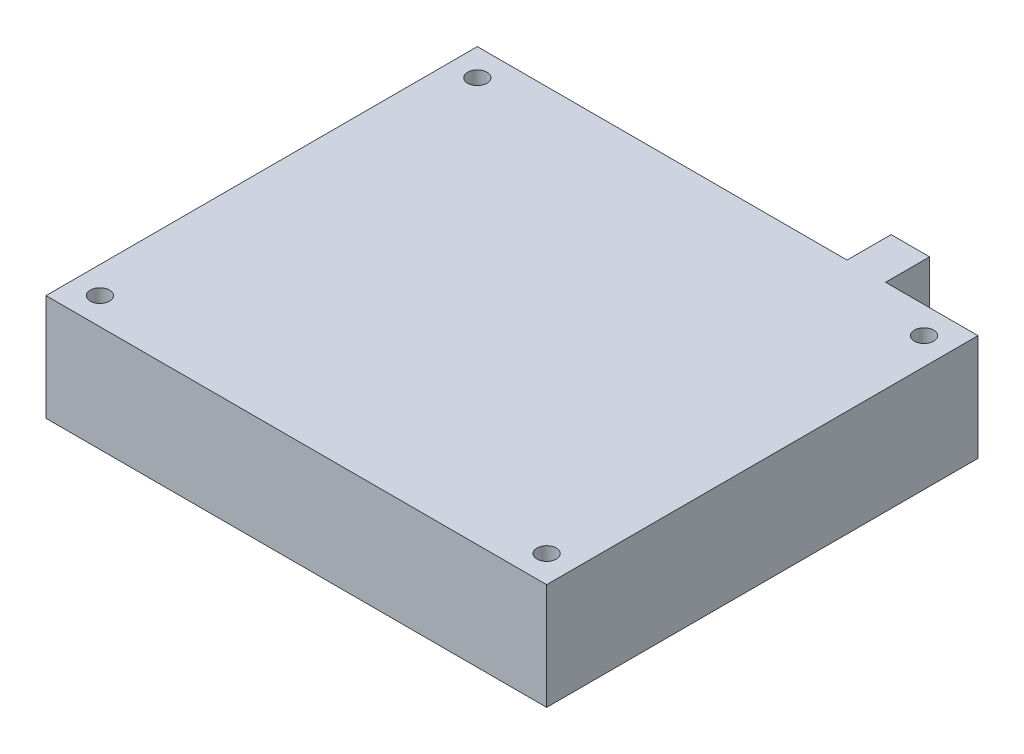
SolidWorks part; units mm, degrees
material "聚脂树脂"
ref_plane "前视基准面" through (0, 0, 0) normal (0, 0, 1) x (1, 0, 0)
ref_plane "上视基准面" through (0, 0, 0) normal (0, 1, 0) x (1, 0, 0)
ref_plane "右视基准面" through (0, 0, 0) normal (1, 0, 0) x (0, 0, -1)
other "Configuration Table"
sketch "草图1" plane through (0, 0, 0) normal (0, 1, 0) x (1, 0, 0)
  line L0 (0, 0) -> (0, 37.0245) construction
  line L1 (-32.5, -28) -> (32.5, -28)
  line L2 (-32.5, -28) -> (-32.5, 28)
  line L3 (-32.5, 28) -> (32.5, 28)
  line L4 (32.5, -28) -> (32.5, 28)
  line L5 (-32.5, -28) -> (32.5, 28) construction
  line L6 (-32.5, 28) -> (32.5, -28) construction
  line L7 (0, 0) -> (44.4454, 0) construction
  circle A0 centre (-29, 24.5) radius 1.25
  circle A1 centre (29, 24.5) radius 1.25
  circle A2 centre (29, -24.5) radius 1.25
  circle A3 centre (-29, -24.5) radius 1.25
  point P0 (0, 0)
  dimension "D3" = 2.5
  dimension "D4" = 58
  dimension "D5" = 49
  dimension "D1" = 65
  dimension "D2" = 56
extrude "凸台-拉伸1" add sketch "草图1" along normal blind 13.8
sketch "草图2" plane through (0, 13.8, 0) normal (0, 1, 0) x (1, 0, 0)
  line L0 (15.5, 28) -> (15.5, 33.72)
  line L1 (32.5, 28) -> (-32.5, 28) construction
  line L2 (15.5, 33.72) -> (20.5, 33.72)
  line L3 (20.5, 33.72) -> (20.5, 28)
  line L4 (20.5, 28) -> (15.5, 28)
  line L5 (32.5, -28) -> (32.5, 28) construction
  dimension "D1" = 5.72
  dimension "D2" = 5
  dimension "D3" = 12
extrude "凸台-拉伸2" add sketch "草图2" against normal up to surface (13.8 mm away) up to face at (29, 0, 25.75)
